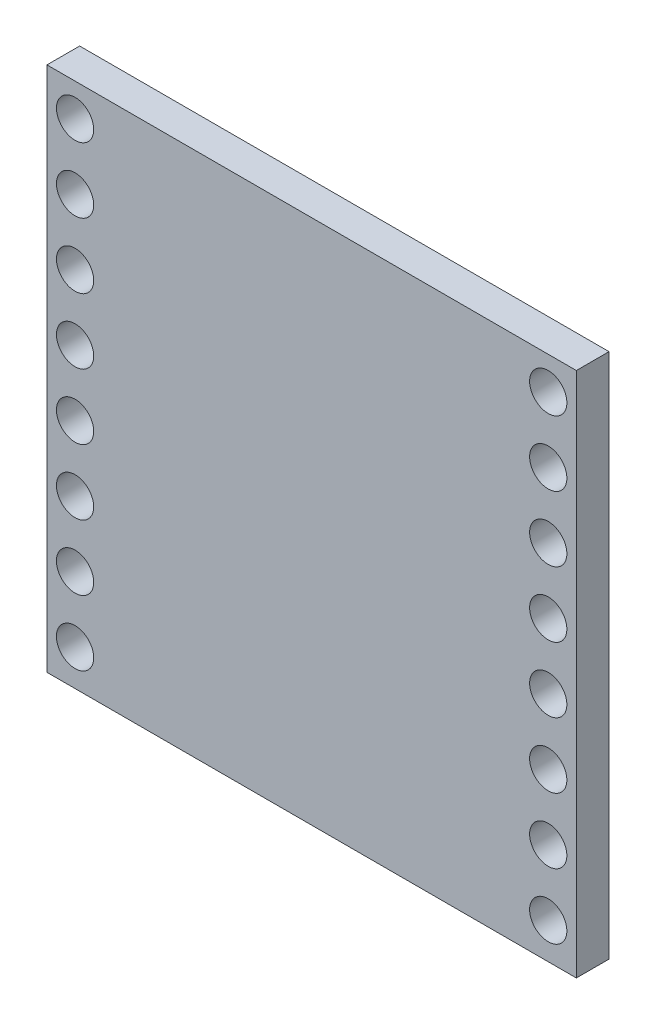
SolidWorks part; units mm, degrees
ref_plane "Alzado" through (0, 0, 0) normal (0, 0, 1) x (1, 0, 0)
ref_plane "Planta" through (0, 0, 0) normal (0, 1, 0) x (1, 0, 0)
ref_plane "Vista lateral" through (0, 0, 0) normal (1, 0, 0) x (0, 0, -1)
sketch "Croquis1" plane through (0, 0, 0) normal (0, 0, 1) x (1, 0, 0)
  line L0 (0, 8.05) -> (0, -8.05) construction
  line L1 (8.1, -8.05) -> (-8.1, -8.05)
  line L2 (8.1, -8.05) -> (8.1, 8.05)
  line L3 (8.1, 8.05) -> (-8.1, 8.05)
  line L4 (-8.1, -8.05) -> (-8.1, 8.05)
  line L5 (8.1, -8.05) -> (-8.1, 8.05) construction
  line L6 (8.1, 8.05) -> (-8.1, -8.05) construction
  circle A0 centre (-7.24, 7.05) radius 0.57
  circle A1 centre (-7.24, 5.05) radius 0.57
  circle A2 centre (-7.24, 3.05) radius 0.57
  circle A3 centre (-7.24, 1.05) radius 0.57
  circle A4 centre (-7.24, -0.95) radius 0.57
  circle A5 centre (-7.24, -2.95) radius 0.57
  circle A6 centre (-7.24, -4.95) radius 0.57
  circle A7 centre (-7.24, -6.95) radius 0.57
  circle A8 centre (7.24, -6.95) radius 0.57
  circle A9 centre (7.24, -4.95) radius 0.57
  circle A10 centre (7.24, -2.95) radius 0.57
  circle A11 centre (7.24, -0.95) radius 0.57
  circle A12 centre (7.24, 1.05) radius 0.57
  circle A13 centre (7.24, 3.05) radius 0.57
  circle A14 centre (7.24, 5.05) radius 0.57
  circle A15 centre (7.24, 7.05) radius 0.57
  point P0 (0, 0)
  dimension "D3" = 1.14
  dimension "D6" = 1
  dimension "D1" = 16.2
  dimension "D2" = 16.1
  dimension "D4" = 0.86
  dimension "D5" = 8
extrude "Saliente-Extruir1" add sketch "Croquis1" along normal blind 1
